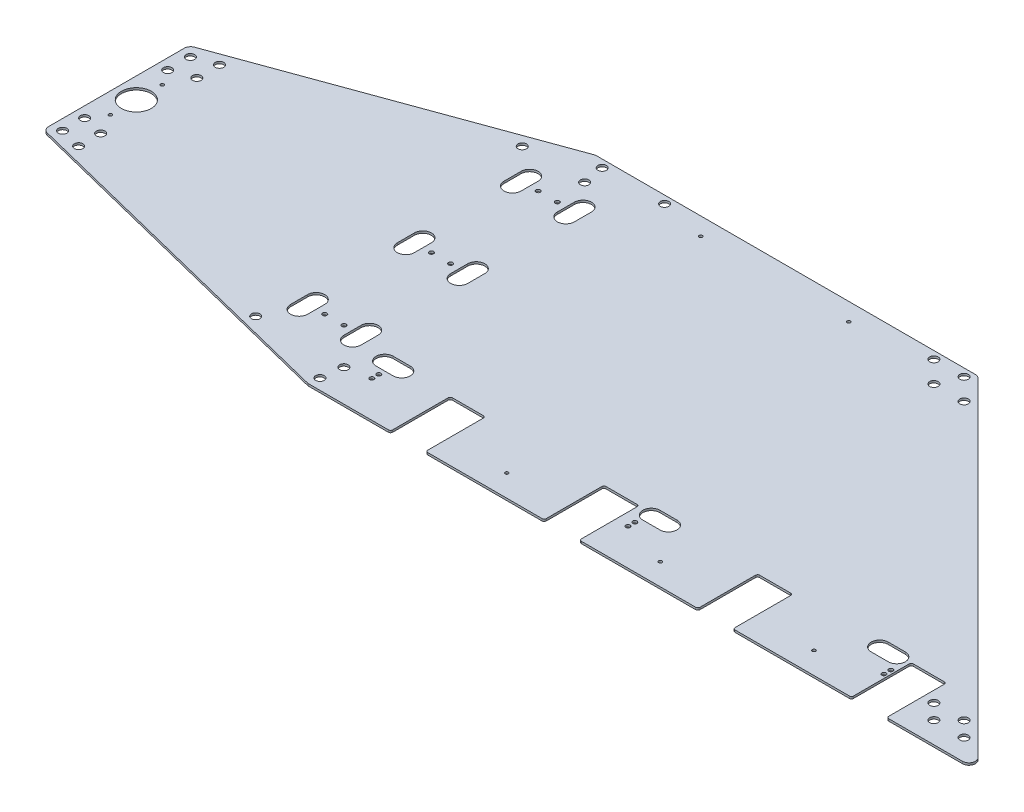
SolidWorks part; units mm, degrees
material "PC High Viscosity"
ref_plane "Front Plane" through (0, 0, 0) normal (0, 0, 1) x (1, 0, 0)
ref_plane "Top Plane" through (0, 0, 0) normal (0, 1, 0) x (1, 0, 0)
ref_plane "Right Plane" through (0, 0, 0) normal (1, 0, 0) x (0, 0, -1)
sketch "Sketch2" plane through (0, 0, 0) normal (0, 1, 0) x (1, 0, 0)
  line L5 (993.5568, 0) -> (0.4168, 0) construction
  line L6 (-516.6797, 128.8227) -> (-1.1348, 0.2829)
  line L7 (1.1695, 0) -> (973.9292, 0)
  line L8 (491.7144, 505.2102) -> (980.6644, 16.2602)
  line L9 (-78.5666, 508) -> (484.9792, 508)
  line L10 (-81.8243, 507.4256) -> (-517.6331, 348.8041)
  line L11 (-523.9004, 339.8536) -> (-523.9004, 138.0648)
  line L36 (122.8448, 0) -> (122.8448, 88.9)
  line L37 (122.8448, 88.9) -> (175.1688, 88.9)
  line L38 (175.1688, 0) -> (175.1688, 88.9)
  line L49 (351.4448, 0) -> (351.4448, 88.9)
  line L50 (351.4448, 88.9) -> (403.7688, 88.9)
  line L51 (403.7688, 0) -> (403.7688, 88.9)
  line L57 (580.0448, 0) -> (580.0448, 88.9)
  line L58 (580.0448, 88.9) -> (632.3688, 88.9)
  line L59 (632.3688, 0) -> (632.3688, 88.9)
  line L61 (808.6448, 0) -> (808.6448, 88.9)
  line L62 (808.6448, 88.9) -> (860.9688, 88.9)
  line L63 (860.9688, 0) -> (860.9688, 88.9)
  arc A0 (-517.6331, 348.8041) -> (-523.9004, 339.8536) centre (-514.3754, 339.8536) ccw
  arc A1 (-523.9004, 138.0648) -> (-516.6797, 128.8227) centre (-514.3754, 138.0648) ccw
  arc A2 (-1.1348, 0.2829) -> (1.1695, 0) centre (1.1695, 9.525) ccw
  arc A3 (980.6644, 16.2602) -> (973.9292, 0) centre (973.9292, 9.525) cw
  arc A4 (491.7144, 505.2102) -> (484.9792, 508) centre (484.9792, 498.475) ccw
  arc A5 (-81.8243, 507.4256) -> (-78.5666, 508) centre (-78.5666, 498.475) cw
  circle A6 centre (133.2169, 15.875) radius 7.62
  circle A7 centre (5.8746, 47.625) radius 6.35
  circle A8 centre (1.9762, 15.875) radius 6.35
  circle A9 centre (-125.3661, 47.625) radius 6.35
  circle A10 centre (-508.0254, 175.7547) radius 6.35
  circle A11 centre (-508.0254, 143.0327) radius 6.35
  circle A12 centre (-476.2754, 167.8385) radius 6.35
  circle A13 centre (-476.2754, 135.1165) radius 6.35
  circle A14 centre (-508.0254, 333.1213) radius 6.35
  circle A15 centre (-476.2754, 344.6773) radius 6.35
  circle A16 centre (-476.2754, 310.8897) radius 6.35
  circle A17 centre (-508.0254, 299.3336) radius 6.35
  circle A18 centre (-146.0386, 464.8731) radius 6.35
  circle A19 centre (-58.8062, 496.6231) radius 6.35
  circle A20 centre (-53.2079, 464.8731) radius 6.35
  circle A21 centre (34.0246, 496.6231) radius 6.35
  circle A22 centre (434.692, 496.623) radius 6.35
  circle A23 centre (466.4419, 464.873) radius 6.35
  circle A24 centre (479.5932, 496.623) radius 6.35
  circle A25 centre (511.3432, 464.873) radius 6.35
  circle A26 centre (877.3398, 53.975) radius 6.35
  circle A27 centre (922.2411, 53.975) radius 6.35
  circle A28 centre (899.5648, 31.75) radius 6.35
  circle A29 centre (944.4661, 31.75) radius 6.35
  circle A31 centre (322.9287, 481.637) radius 2.4575
  circle A32 centre (263.3068, 32.385) radius 2.4575
  circle A33 centre (491.9068, 32.385) radius 2.4575
  circle A34 centre (720.5068, 32.385) radius 2.4575
  circle A35 centre (-493.0394, 276.2907) radius 2.4574
  circle A36 centre (-493.0394, 199.0909) radius 2.4574
  circle A37 centre (102.7505, 481.637) radius 2.4575
  point P8 (-523.9004, 346.523)
  point P18 (-523.9004, 130.623)
  point P21 (0, 0)
  point P24 (996.9246, 0)
  dimension "D9" = 9.525
  dimension "D11" = 121.6753
  dimension "D12" = 52.324
  dimension "D13" = 176.276
  dimension "D14" = 176.276
  dimension "D15" = 176.276
  dimension "D16" = 220.1782
  dimension "D39" = 12.7
  dimension "D45" = 15.24
  dimension "D35" = 4.9149
  dimension "D51" = 4.9149
  dimension "D53" = 4.9149
  dimension "D1" = 523.9004
  dimension "D2" = 508
  dimension "D3" = 1520.825
  dimension "D4" = 166
  dimension "D5" = 160
  dimension "D6" = 110
  dimension "D7" = 215.9
  dimension "D8" = 45
  dimension "D10" = 531.3276
  dimension "D24" = 88.9
  dimension "D25" = 199.0909
  dimension "D29" = 77.1998
  dimension "D30" = 88.9
  dimension "D31" = 88.9
  dimension "D32" = 88.9
extrude "Boss-Extrude1" add sketch "Sketch2" along normal blind 3.175
fillet "Fillet1" radius 3.175 16 edges at (175.1688, 1.5875, -88.9) (122.8448, 1.5875, -88.9) (351.4448, 1.5875, -88.9) (403.7688, 1.5875, -88.9) (632.3688, 1.5875, -88.9) (580.0448, 1.5875, -88.9) (860.9688, 1.5875, -88.9) (808.6448, 1.5875, -88.9) (632.3688, 1.5875, 0) (580.0448, 1.5875, 0) (403.7688, 1.5875, 0) (351.4448, 1.5875, 0) (175.1688, 1.5875, 0) (122.8448, 1.5875, 0) (860.9688, 1.5875, 0) (808.6448, 1.5875, 0)
sketch "Sketch6" plane through (0, 3.175, 0) normal (0, 1, 0) x (1, 0, 0)
  line L0 (-22.6592, 431.8127) -> (-22.6592, 406.4127) construction
  line L1 (-9.9592, 431.8127) -> (-9.9592, 406.4127)
  line L2 (-35.3592, 431.8127) -> (-35.3592, 406.4127)
  line L3 (-102.0342, 431.8127) -> (-102.0342, 406.4127) construction
  line L4 (-89.3342, 431.8127) -> (-89.3342, 406.4127)
  line L5 (-114.7342, 431.8127) -> (-114.7342, 406.4127)
  line L6 (-22.6592, 273.0627) -> (-22.6592, 247.6627) construction
  line L7 (-9.9592, 273.0627) -> (-9.9592, 247.6627)
  line L8 (-35.3592, 273.0627) -> (-35.3592, 247.6627)
  line L9 (-102.0342, 273.0627) -> (-102.0342, 247.6627) construction
  line L10 (-89.3342, 273.0627) -> (-89.3342, 247.6627)
  line L11 (-114.7342, 273.0627) -> (-114.7342, 247.6627)
  line L12 (-22.6592, 114.3127) -> (-22.6592, 88.9127) construction
  line L13 (-9.9592, 114.3127) -> (-9.9592, 88.9127)
  line L14 (-35.3592, 114.3127) -> (-35.3592, 88.9127)
  line L15 (-102.0342, 114.3127) -> (-102.0342, 88.9127) construction
  line L16 (-89.3342, 114.3127) -> (-89.3342, 88.9127)
  line L17 (-114.7342, 114.3127) -> (-114.7342, 88.9127)
  arc A0 (-9.9592, 431.8127) -> (-35.3592, 431.8127) centre (-22.6592, 431.8127) ccw
  arc A1 (-35.3592, 406.4127) -> (-9.9592, 406.4127) centre (-22.6592, 406.4127) ccw
  arc A2 (-89.3342, 431.8127) -> (-114.7342, 431.8127) centre (-102.0342, 431.8127) ccw
  arc A3 (-114.7342, 406.4127) -> (-89.3342, 406.4127) centre (-102.0342, 406.4127) ccw
  arc A4 (-9.9592, 273.0627) -> (-35.3592, 273.0627) centre (-22.6592, 273.0627) ccw
  arc A5 (-35.3592, 247.6627) -> (-9.9592, 247.6627) centre (-22.6592, 247.6627) ccw
  arc A6 (-89.3342, 273.0627) -> (-114.7342, 273.0627) centre (-102.0342, 273.0627) ccw
  arc A7 (-114.7342, 247.6627) -> (-89.3342, 247.6627) centre (-102.0342, 247.6627) ccw
  arc A8 (-9.9592, 114.3127) -> (-35.3592, 114.3127) centre (-22.6592, 114.3127) ccw
  arc A9 (-35.3592, 88.9127) -> (-9.9592, 88.9127) centre (-22.6592, 88.9127) ccw
  arc A10 (-89.3342, 114.3127) -> (-114.7342, 114.3127) centre (-102.0342, 114.3127) ccw
  arc A11 (-114.7342, 88.9127) -> (-89.3342, 88.9127) centre (-102.0342, 88.9127) ccw
  point P1 (-76.6342, 419.1127)
  point P2 (-48.0592, 260.3627)
  point P3 (-76.6342, 260.3627)
  point P4 (-76.6342, 101.6127)
  point P5 (-48.0592, 101.6127)
  point P6 (-48.0592, 419.1127)
  point P8 (-22.6592, 419.1127)
  point P13 (-102.0342, 419.1127)
  point P24 (-22.6592, 260.3627)
  point P31 (-102.0342, 260.3627)
  point P38 (-22.6592, 101.6127)
  point P45 (-102.0342, 101.6127)
  dimension "D1" = 25.4
  dimension "D2" = 25.4
  dimension "D3" = 12.7
  dimension "D5" = 12.7
extrude "Cut-Extrude1" cut sketch "Sketch6" against normal blind 6.35
hole_wizard "1/4 (0.25) Diameter Hole1" positions "3DSketch1" profile "Sketch7" hole size "1/4" standard "ANSI Inch" end condition through all
sketch3d "3DSketch1"
  point P0 (-48.0592, 3.175, -419.1127)
  point P3 (-76.6342, 3.175, -419.1127)
  point P6 (-76.6342, 3.175, -260.3627)
  point P9 (-48.0592, 3.175, -260.3627)
  point P12 (-48.0592, 3.175, -101.6127)
  point P15 (-76.6342, 3.175, -101.6127)
sketch "Sketch7" plane through (-48.0592, 3.175, -419.1127) normal (1, 0, 0) x (0, 0, 1)
  line L0 (0, 0) -> (0, 3.175)
  line L1 (0, 3.175) -> (3.175, 3.175)
  line L2 (3.175, 3.175) -> (3.175, 0)
  line L5 (3.175, 0) -> (0, 0)
  line L11 (0, -6.35) -> (0, 107.95) construction
  dimension "Thru Hole Dia." = 6.35
  dimension "Thru Hole Depth" = 3.175
sketch "Sketch8" plane through (0, 3.175, 0) normal (0, 1, 0) x (1, 0, 0)
  line L0 (-493.0394, 276.2907) -> (-493.0394, 199.0909) construction
  circle A0 centre (-493.0394, 237.6908) radius 22.225
  point P0 (-493.0394, 237.6908)
  dimension "D1" = 44.45
extrude "Cut-Extrude2" cut sketch "Sketch8" against normal through all
sketch "Sketch9" plane through (0, 3.175, 0) normal (0, 1, 0) x (1, 0, 0)
  line L0 (1.1695, 0) -> (119.6698, 0) construction
  line L1 (122.8448, 3.175) -> (122.8448, 85.725) construction
  line L2 (403.7688, 3.175) -> (403.7688, 85.725) construction
  line L3 (808.6448, 3.175) -> (808.6448, 85.725) construction
  point P0 (41.0568, 53.975)
  point P1 (422.0568, 53.975)
  point P2 (803.0568, 53.975)
  dimension "D1" = 53.975
  dimension "D2" = 81.788
  dimension "D3" = 18.288
  dimension "D4" = 5.588
hole_wizard "1/4 (0.25) Diameter Hole2" positions "Sketch10" profile "Sketch11" hole size "1/4" standard "ANSI Inch" end condition through all
sketch "Sketch10" plane through (0, 3.175, 0) normal (0, 1, 0) x (1, 0, 0)
  point P0 (41.0568, 53.975)
  point P3 (422.0568, 53.975)
  point P6 (803.0568, 53.975)
  point P10 (41.0568, 64.2938)
  point P12 (422.0568, 64.2938)
  point P14 (803.0568, 64.2938)
  dimension "D1" = 10.3187
sketch "Sketch11" plane through (41.0568, 3.175, -53.975) normal (1, 0, 0) x (0, 0, 1)
  line L0 (0, 0) -> (0, 3.175)
  line L1 (0, 3.175) -> (3.175, 3.175)
  line L2 (3.175, 3.175) -> (3.175, 0)
  line L5 (3.175, 0) -> (0, 0)
  line L11 (0, -6.35) -> (0, 107.95) construction
  dimension "Thru Hole Dia." = 6.35
  dimension "Thru Hole Depth" = 3.175
sketch "Sketch12" plane through (0, 3.175, 0) normal (0, 1, 0) x (1, 0, 0)
  line L0 (28.3568, 85.725) -> (53.7568, 85.725) construction
  line L1 (28.3568, 98.425) -> (53.7568, 98.425)
  line L2 (28.3568, 73.025) -> (53.7568, 73.025)
  line L3 (425.2318, 85.725) -> (450.6318, 85.725) construction
  line L4 (425.2318, 98.425) -> (450.6318, 98.425)
  line L5 (425.2318, 73.025) -> (450.6318, 73.025)
  line L6 (764.9568, 85.725) -> (790.3568, 85.725) construction
  line L7 (764.9568, 98.425) -> (790.3568, 98.425)
  line L8 (764.9568, 73.025) -> (790.3568, 73.025)
  arc A0 (28.3568, 98.425) -> (28.3568, 73.025) centre (28.3568, 85.725) ccw
  arc A1 (53.7568, 73.025) -> (53.7568, 98.425) centre (53.7568, 85.725) ccw
  arc A2 (425.2318, 98.425) -> (425.2318, 73.025) centre (425.2318, 85.725) ccw
  arc A3 (450.6318, 73.025) -> (450.6318, 98.425) centre (450.6318, 85.725) ccw
  arc A4 (764.9568, 98.425) -> (764.9568, 73.025) centre (764.9568, 85.725) ccw
  arc A5 (790.3568, 73.025) -> (790.3568, 98.425) centre (790.3568, 85.725) ccw
  circle A6 centre (720.5068, 32.385) radius 2.4575 construction
  circle A7 centre (491.9068, 32.385) radius 2.4575 construction
  circle A8 centre (263.3068, 32.385) radius 2.4575 construction
  circle A9 centre (720.5068, 32.385) radius 2.4575
  circle A10 centre (491.9068, 32.385) radius 2.4575
  circle A11 centre (263.3068, 32.385) radius 2.4575
  circle A12 centre (41.0568, 53.975) radius 3.175 construction
  circle A13 centre (422.0568, 53.975) radius 3.175 construction
  circle A14 centre (803.0568, 53.975) radius 3.175 construction
  circle A15 centre (41.0568, 53.975) radius 3.175
  circle A16 centre (422.0568, 53.975) radius 3.175
  circle A17 centre (803.0568, 53.975) radius 3.175
  point P2 (41.0568, 85.725)
  point P7 (437.9318, 85.725)
  point P14 (777.6568, 85.725)
  dimension "D1" = 12.7
  dimension "D2" = 25.4
  dimension "D3" = 31.75
  dimension "D4" = 12.7
  dimension "D5" = 3.175
extrude "Cut-Extrude3" cut sketch "Sketch12" against normal through all
